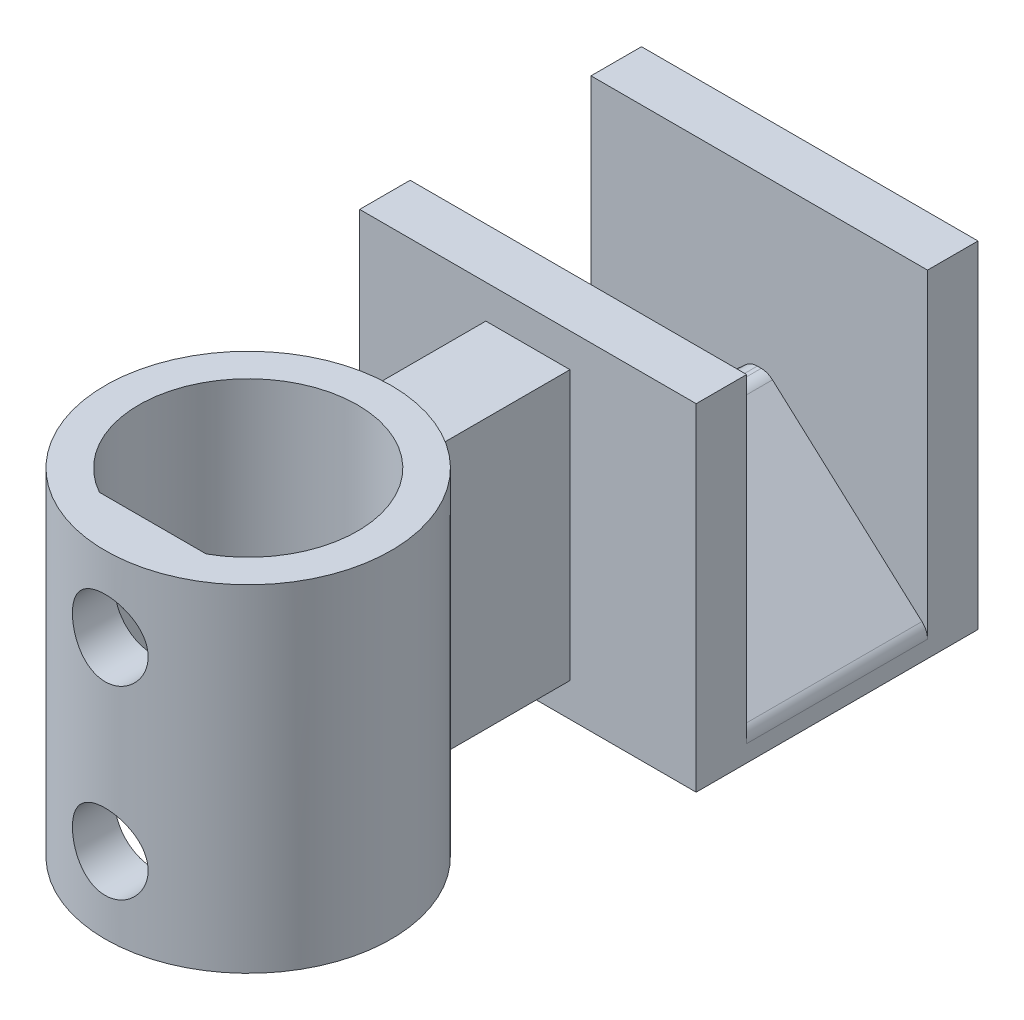
SolidWorks part; units mm, degrees
ref_plane "Front Plane" through (0, 0, 0) normal (0, 0, 1) x (1, 0, 0)
ref_plane "Top Plane" through (0, 0, 0) normal (0, 1, 0) x (1, 0, 0)
ref_plane "Right Plane" through (0, 0, 0) normal (1, 0, 0) x (0, 0, -1)
sketch "Sketch2" plane through (0, 0, 0) normal (0, 0, 1) x (1, 0, 0)
  line L1 (-10, -5) -> (10, -5)
  line L2 (-10, -5) -> (-10, 5)
  line L3 (-10, 5) -> (10, 5)
  line L4 (10, -5) -> (10, 5)
  line L5 (-10, -5) -> (10, 5) construction
  line L6 (-10, 5) -> (10, -5) construction
  point P0 (0, 0)
  dimension "D1" = 10
  dimension "D2" = 20
extrude "Boss-Extrude1" add sketch "Sketch2" along normal mid plane 10.75
chamfer "Chamfer1" distance 9.5 angle 42 2 edges at (10, 5, 0) (-10, 5, 0)
fillet "Fillet3" radius 1 4 edges at (-10, -3.5538, 0) (10, -3.5538, 0) (0.5, 5, 0) (-0.5, 5, 0)
sketch "Sketch3" plane through (0, 0, 5.375) normal (0, 0, 1) x (1, 0, 0)
  line L0 (-10, -5) -> (10, -5) construction
  line L1 (-10, 15) -> (10, 15)
  line L2 (-10, 15) -> (-10, -5)
  line L3 (-10, -5) -> (10, -5)
  line L4 (10, 15) -> (10, -5)
  line L5 (-10, 15) -> (10, -5) construction
  line L6 (-10, -5) -> (10, 15) construction
  point P0 (0, 5)
  dimension "D1" = 20
  dimension "D2" = 20
extrude "Boss-Extrude2" add sketch "Sketch3" along normal blind 3
mirror "Mirror1" about plane through (0, 0, 0) normal (0, 0, 1) of "Boss-Extrude2"
sketch "Sketch6" plane through (0, 0, 0) normal (0, 1, 0) x (1, 0, 0)
  line L0 (-3.175, -30.6718) -> (3.175, -30.6718)
  arc A0 (3.175, -30.6718) -> (-3.175, -30.6718) centre (0, -25) ccw
  circle A1 centre (0, -25) radius 8.5
  dimension "D1" = 13
  dimension "D2" = 2
  dimension "D3" = 25
  dimension "D4" = 6.35
extrude "Boss-Extrude3" add sketch "Sketch6" along normal up to surface and the other way up to surface separate body up to face at (0, 15, 6.875) other way up to face at (0, -5, 0)
sketch "Sketch5" plane through (0, 0, 8.375) normal (0, 0, 1) x (1, 0, 0)
  line L0 (-10, -5) -> (10, -5) construction
  line L1 (-2.5, 13) -> (2.5, 13)
  line L2 (-2.5, 13) -> (-2.5, -3)
  line L3 (-2.5, -3) -> (2.5, -3)
  line L4 (2.5, 13) -> (2.5, -3)
  line L5 (-2.5, 13) -> (2.5, -3) construction
  line L6 (-2.5, -3) -> (2.5, 13) construction
  line L7 (10, 15) -> (-10, 15) construction
  point P0 (0, 5)
  dimension "D1" = 2
  dimension "D2" = 2
  dimension "D3" = 5
extrude "Boss-Extrude4" add sketch "Sketch5" along normal up to surface (8.501 mm away)
ref_plane "Plane1" through (0, 0, 20) normal (0, 0, 1) x (1, 0, 0)
sketch "Sketch7" plane through (0, 0, 20) normal (0, 0, 1) x (1, 0, 0)
  line L0 (-8.5, -5) -> (8.5, -5) construction
  line L1 (6.5, 15) -> (-6.5, 15) construction
  circle A0 centre (0, 10.5) radius 2.25
  circle A1 centre (0, -0.5) radius 2.25
  dimension "D1" = 4.5
  dimension "D2" = 4.5
  dimension "D3" = 4.5
  dimension "D4" = 4.5
extrude "Cut-Extrude1" cut sketch "Sketch7" along normal up to surface (13.1968 mm away)
